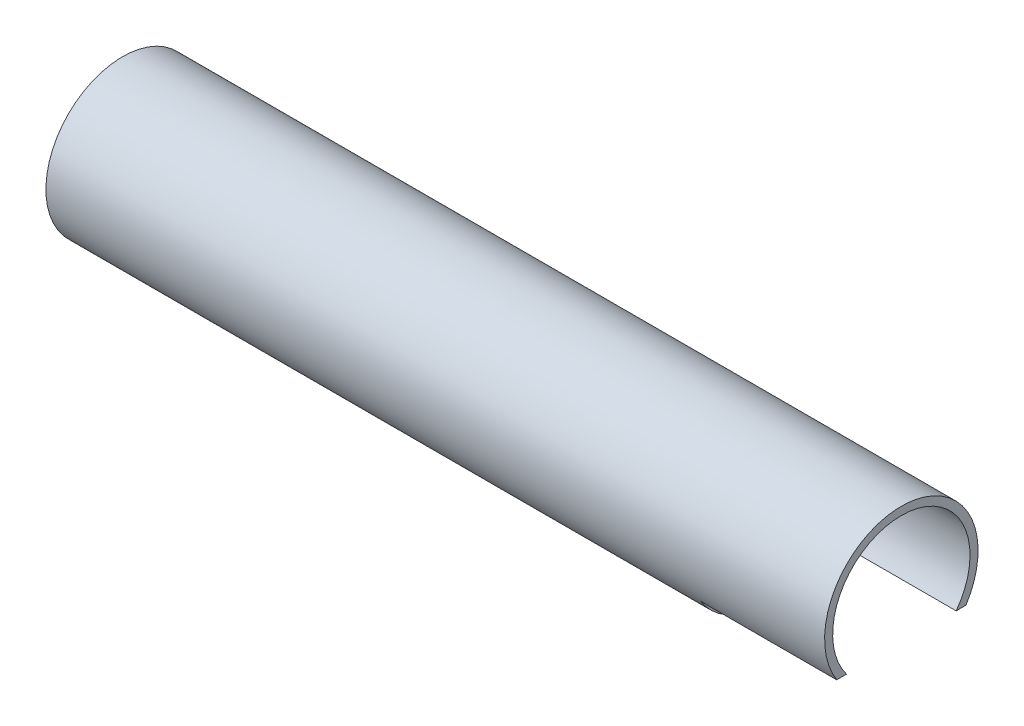
SolidWorks part; units mm, degrees
ref_plane "Front" through (0, 0, 0) normal (0, 0, 1) x (1, 0, 0)
ref_plane "Top" through (0, 0, 0) normal (0, 1, 0) x (1, 0, 0)
ref_plane "Right" through (0, 0, 0) normal (1, 0, 0) x (0, 0, -1)
sketch "Croquis1" plane through (0, 0, 0) normal (1, 0, 0) x (0, 0, -1)
  circle A1 centre (0, 0) radius 57.15
  circle A2 centre (0, 0) radius 51.15
  dimension "D1" = 114.3
  dimension "D2" = 6
extrude "Saliente-Extruir1" add sketch "Croquis1" along normal blind 580
sketch "Croquis2" plane through (580, 0, 0) normal (1, 0, 0) x (0, 0, -1)
  line L0 (-48.1402, -30.8) -> (48.1402, -30.8)
  arc A2 (-48.1402, -30.8) -> (48.1402, -30.8) centre (0, 0) ccw
  arc A3 (-40.8373, -30.8) -> (40.8373, -30.8) centre (0, 0) ccw
extrude "Cortar-Extruir1" cut sketch "Croquis2" against normal blind 101.6
